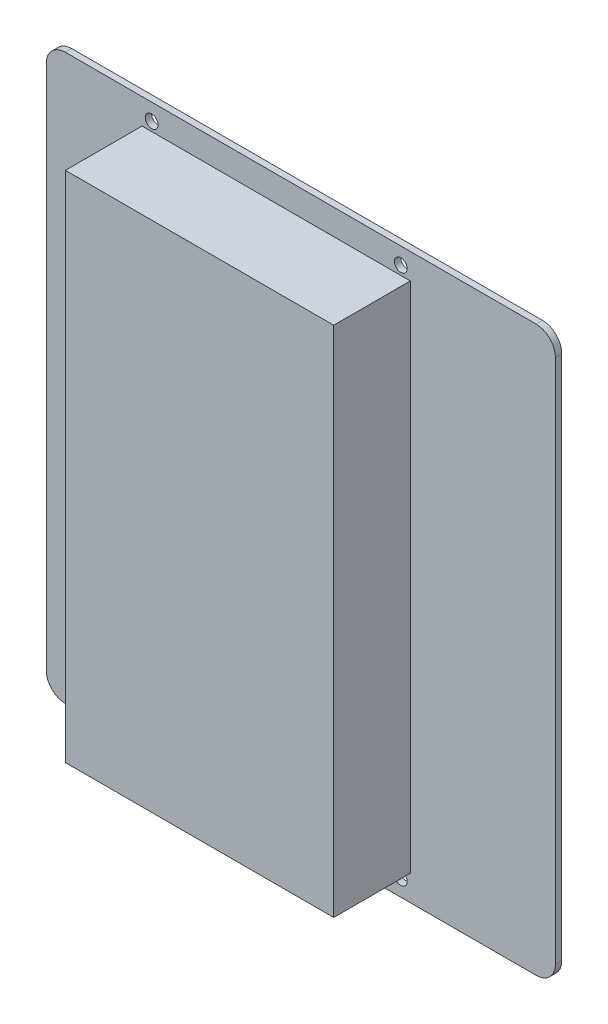
SolidWorks part; units mm, degrees
ref_plane "Front Plane" through (0, 0, 0) normal (0, 0, 1) x (1, 0, 0)
ref_plane "Top Plane" through (0, 0, 0) normal (0, 1, 0) x (1, 0, 0)
ref_plane "Right Plane" through (0, 0, 0) normal (1, 0, 0) x (0, 0, -1)
sketch "Sketch1" plane through (0, 0, 0) normal (0, 0, 1) x (1, 0, 0)
  line L0 (0, 121.439) -> (0, -129.4022) construction
  line L1 (-57.9545, 0) -> (61.9361, 0) construction
  line L2 (-46.7995, 56.0705) -> (46.7995, 56.0705)
  line L3 (50.6095, 52.2605) -> (50.6095, -52.2605)
  line L4 (46.7995, -56.0705) -> (-46.7995, -56.0705)
  line L5 (-50.6095, -52.2605) -> (-50.6095, 52.2605)
  arc A0 (-46.7995, -56.0705) -> (-50.6095, -52.2605) centre (-46.7995, -52.2605) cw
  arc A1 (50.6095, -52.2605) -> (46.7995, -56.0705) centre (46.7995, -52.2605) cw
  arc A2 (46.7995, 56.0705) -> (50.6095, 52.2605) centre (46.7995, 52.2605) cw
  arc A3 (-46.7995, 56.0705) -> (-50.6095, 52.2605) centre (-46.7995, 52.2605) ccw
  point P7 (0, 56.0705)
  point P10 (-50.6095, 0)
  point P13 (-50.6095, -56.0705)
  point P20 (-50.6095, 56.0705)
  dimension "D3" = 3.81
  dimension "D1" = 101.219
  dimension "D2" = 112.141
extrude "Boss-Extrude1" add sketch "Sketch1" along normal blind 1.27 contours L2 A2 L3 A1 L4 A0 L5 A3
sketch "Sketch2" plane through (0, 0, 1.27) normal (0, 0, 1) x (1, 0, 0)
  line L0 (-31.5595, 50.9905) -> (21.7805, 50.9905)
  line L2 (21.7805, 50.9905) -> (21.7805, -50.9905)
  line L4 (21.7805, -50.9905) -> (-31.5595, -50.9905)
  line L5 (-31.5595, -50.9905) -> (-31.5595, 50.9905)
  line L6 (-4.8895, 54.5824) -> (-4.8895, -54.7823) construction
  line L8 (-50.6095, -52.2605) -> (-50.6095, 52.2605) construction
  line L9 (-46.7995, 56.0705) -> (46.7995, 56.0705) construction
  line L10 (46.7995, -56.0705) -> (-46.7995, -56.0705) construction
  point P4 (-4.8895, 50.9905)
  point P9 (-4.8895, -50.9905)
  dimension "D1" = 53.34
  dimension "D2" = 19.05
  dimension "D3" = 5.08
  dimension "D4" = 5.08
extrude "Boss-Extrude2" add sketch "Sketch2" along normal blind 15.24
sketch "Sketch4" plane through (0, 0, 1.27) normal (0, 0, 1) x (1, 0, 0)
  line L0 (-46.7995, 56.0705) -> (46.7995, 56.0705) construction
  line L1 (-50.6095, -52.2605) -> (-50.6095, 52.2605) construction
  circle A0 centre (-29.6545, 52.7685) radius 1.27
  circle A1 centre (19.8755, 52.7685) radius 1.27
  circle A2 centre (-29.6545, -52.7685) radius 1.27
  circle A3 centre (19.8755, -52.7685) radius 1.27
  dimension "D5" = 2.54
  dimension "D6" = 2.54
  dimension "D7" = 2.54
  dimension "D8" = 2.54
  dimension "D1" = 3.302
  dimension "D2" = 108.839
  dimension "D3" = 20.955
  dimension "D4" = 70.485
extrude "Cut-Extrude1" cut sketch "Sketch4" against normal through all and the other way through all
equation "\"D6@Sketch4\"=\"D5@Sketch4\""
equation "\"D7@Sketch4\"=\"D5@Sketch4\""
equation "\"D8@Sketch4\"=\"D5@Sketch4\""
